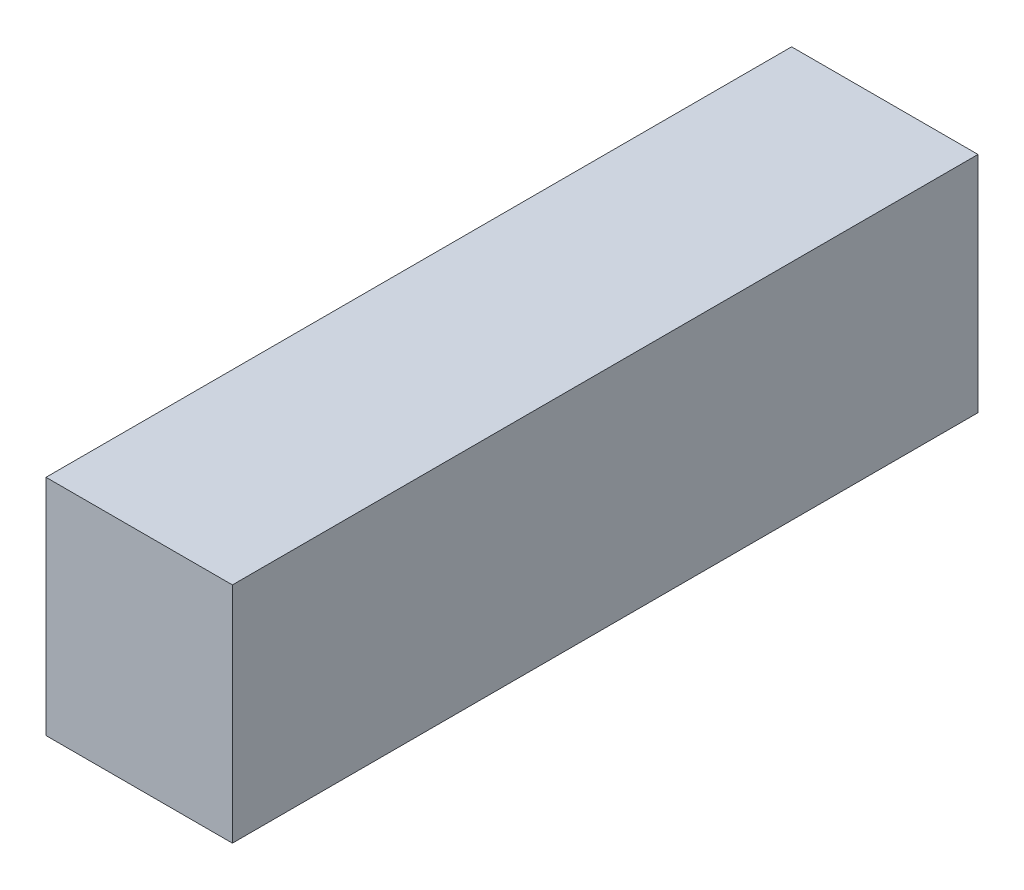
SolidWorks part; units mm, degrees
ref_plane "Front Plane" through (0, 0, 0) normal (0, 0, 1) x (1, 0, 0)
ref_plane "Top Plane" through (0, 0, 0) normal (0, 1, 0) x (1, 0, 0)
ref_plane "Right Plane" through (0, 0, 0) normal (1, 0, 0) x (0, 0, -1)
sketch "Sketch1" plane through (0, 0, 0) normal (0, 0, 1) x (1, 0, 0)
  line L1 (-2.5, 3) -> (2.5, 3)
  line L2 (-2.5, 3) -> (-2.5, -3)
  line L3 (-2.5, -3) -> (2.5, -3)
  line L4 (2.5, 3) -> (2.5, -3)
  line L5 (-2.5, 3) -> (2.5, -3) construction
  line L6 (-2.5, -3) -> (2.5, 3) construction
  point P0 (0, 0)
  dimension "D1" = 6
  dimension "D2" = 5
extrude "Boss-Extrude1" add sketch "Sketch1" along normal blind 20
